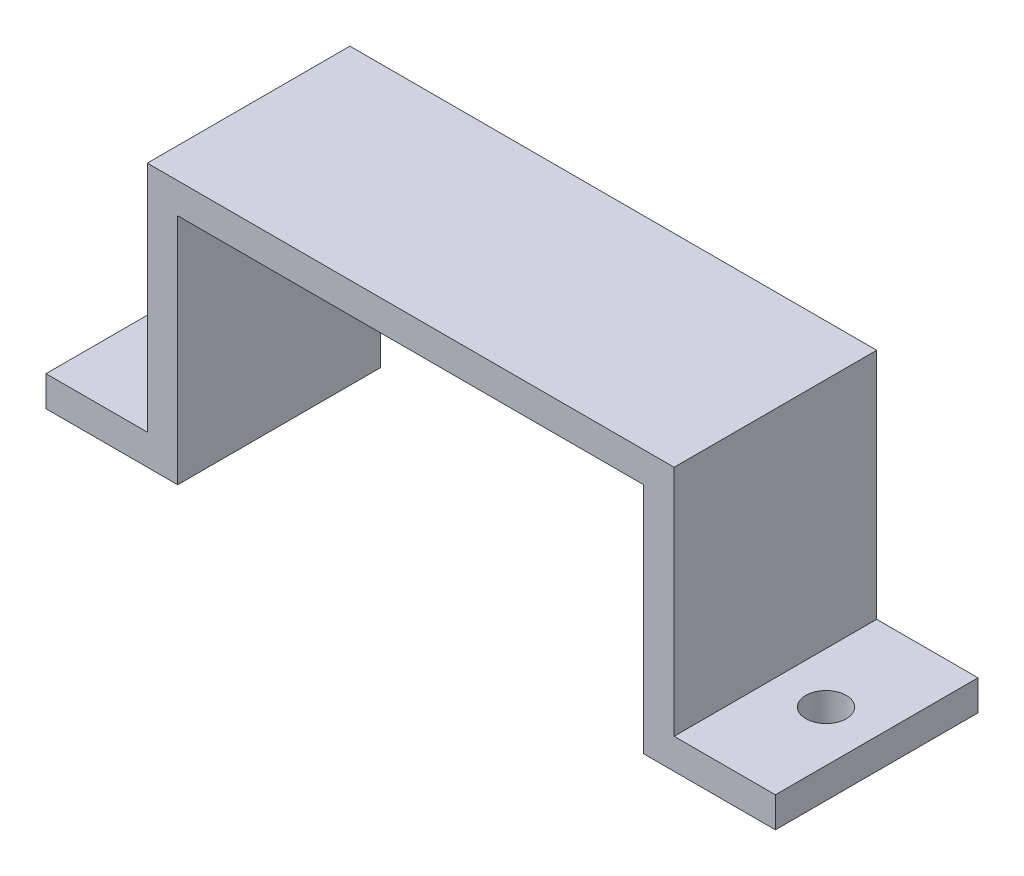
SolidWorks part; units mm, degrees
ref_plane "Front Plane" through (0, 0, 0) normal (0, 0, 1) x (1, 0, 0)
ref_plane "Top Plane" through (0, 0, 0) normal (0, 1, 0) x (1, 0, 0)
ref_plane "Right Plane" through (0, 0, 0) normal (1, 0, 0) x (0, 0, -1)
sketch "Sketch1" plane through (0, 0, 0) normal (0, 0, 1) x (1, 0, 0)
  line L0 (-11.5, 0) -> (-11.5, 10)
  line L1 (-11.5, 10) -> (11.5, 10)
  line L2 (11.5, 10) -> (11.5, 0)
  line L3 (-13, 0) -> (-13, 11.5)
  line L4 (-13, 11.5) -> (13, 11.5)
  line L5 (13, 11.5) -> (13, 0)
  line L6 (-13, 0) -> (-18, 0)
  line L7 (-18, 0) -> (-18, -1.5)
  line L8 (-18, -1.5) -> (-11.5, -1.5)
  line L9 (-11.5, -1.5) -> (-11.5, 0)
  line L10 (0, 0) -> (0, 11.5) construction
  line L11 (11.5, -1.5) -> (11.5, 0)
  line L12 (18, -1.5) -> (11.5, -1.5)
  line L13 (18, 0) -> (18, -1.5)
  line L14 (13, 0) -> (18, 0)
  point P2 (0, 10)
  dimension "D1" = 23
  dimension "D2" = 10
  dimension "D3" = 1.5
  dimension "D4" = 6.5
  dimension "D5" = 1.5
extrude "Boss-Extrude1" add sketch "Sketch1" along normal blind 10
sketch "Sketch2" plane through (0, 0, 0) normal (0, 1, 0) x (1, 0, 0)
  line L0 (-18, -10) -> (-18, 0) construction
  line L1 (-13, 0) -> (-18, 0) construction
  line L2 (0, 0) -> (0, -10) construction
  line L3 (13, -10) -> (-13, -10) construction
  circle A0 centre (-15.5, -5) radius 1
  circle A1 centre (15.5, -5) radius 1
  point P5 (-18, -5)
  point P9 (-15.5, 0)
  dimension "D1" = 2
extrude "Cut-Extrude1" cut sketch "Sketch2" against normal through all both and the other way through all
